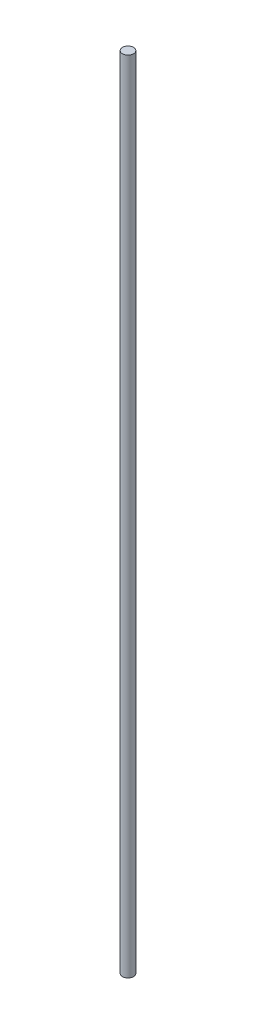
SolidWorks part; units mm, degrees
ref_plane "Front Plane" through (0, 0, 0) normal (0, 0, 1) x (1, 0, 0)
ref_plane "Top Plane" through (0, 0, 0) normal (0, 1, 0) x (1, 0, 0)
ref_plane "Right Plane" through (0, 0, 0) normal (1, 0, 0) x (0, 0, -1)
sketch "Sketch1" plane through (0, 0, 0) normal (0, 1, 0) x (1, 0, 0)
  circle A0 centre (0, 0) radius 3.175
  dimension "D1" = 6.35
extrude "Boss-Extrude1" add sketch "Sketch1" along normal blind 457.2
